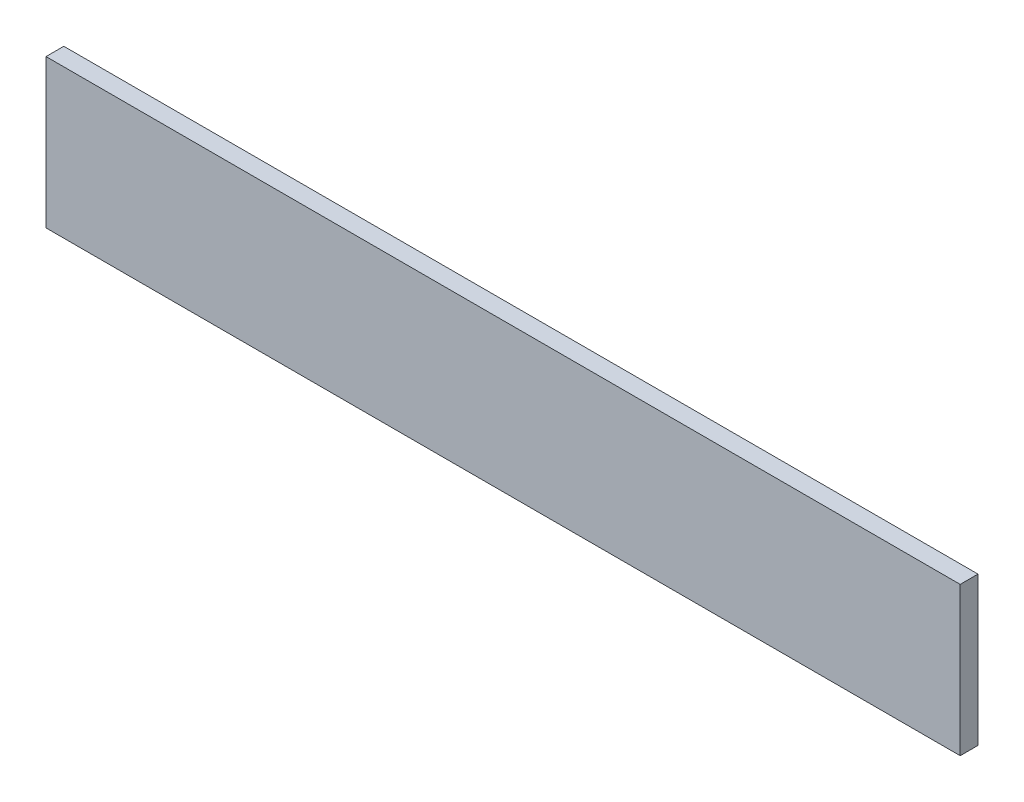
SolidWorks part; units mm, degrees
ref_plane "Front Plane" through (0, 0, 0) normal (0, 0, 1) x (1, 0, 0)
ref_plane "Top Plane" through (0, 0, 0) normal (0, 1, 0) x (1, 0, 0)
ref_plane "Right Plane" through (0, 0, 0) normal (1, 0, 0) x (0, 0, -1)
sketch "Sketch1" plane through (0, 0, 0) normal (0, 0, 1) x (1, 0, 0)
  line L1 (0, 0) -> (154, 0)
  line L2 (0, 0) -> (0, 25)
  line L3 (0, 25) -> (154, 25)
  line L4 (154, 0) -> (154, 25)
  dimension "D1" = 154
  dimension "D2" = 25
extrude "Profile" add sketch "Sketch1" along normal blind 3
equation "\"Profile_Depth\" = 3mm"
equation "\"D1@Profile\" = \"Profile_Depth\""
equation "\"Profile_Sketch_1\" = 154mm"
equation "\"D1@Sketch1\" = \"Profile_Sketch_1\""
equation "\"Profile_Sketch_2\" = 25mm"
equation "\"D2@Sketch1\" = \"Profile_Sketch_2\""
equation "\"EnvelopeWidth\" = 154mm"
equation "\"EnvelopeHeight\" = 25mm"
